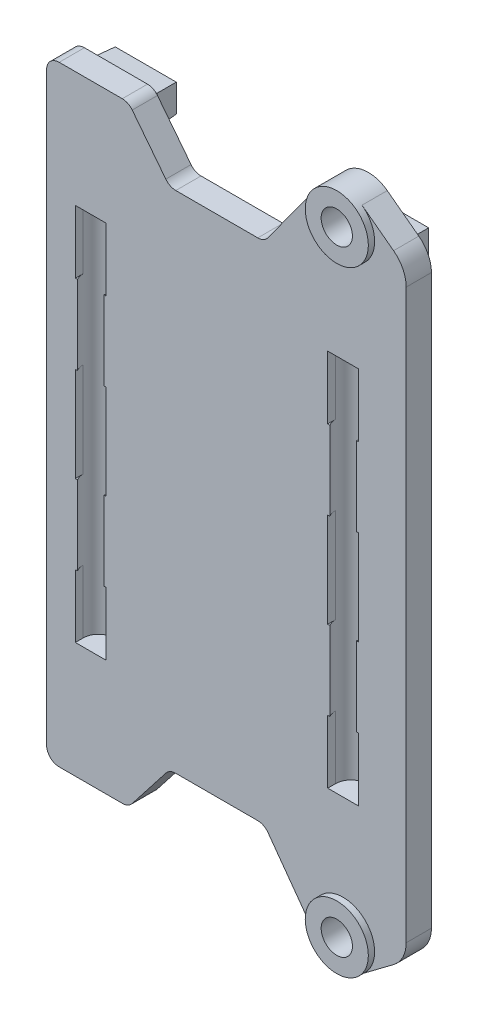
SolidWorks part; units mm, degrees
ref_plane "Front Plane" through (0, 0, 0) normal (0, 0, 1) x (1, 0, 0)
ref_plane "Top Plane" through (0, 0, 0) normal (0, 1, 0) x (1, 0, 0)
ref_plane "Right Plane" through (0, 0, 0) normal (1, 0, 0) x (0, 0, -1)
sketch "Sketch1" plane through (0, 0, 0) normal (0, 0, 1) x (1, 0, 0)
  line L0 (0, 0) -> (190.5, 0) construction
  line L1 (190.5, 28.575) -> (190.5, -28.575) construction
  line L2 (-190.5, -28.575) -> (-190.5, 28.575) construction
  line L3 (190.5, -25.4) -> (-190.5, -25.4) construction
  line L4 (190.5, -25.4) -> (190.5, 25.4) construction
  line L5 (190.5, 25.4) -> (-190.5, 25.4) construction
  line L6 (-190.5, -25.4) -> (-190.5, 25.4) construction
  line L7 (190.5, -25.4) -> (-190.5, 25.4) construction
  line L8 (190.5, 25.4) -> (-190.5, -25.4) construction
  dimension "D1" = 50.8
sketch "Sketch2" plane through (0, 0, 0) normal (0, 0, 1) x (1, 0, 0)
  line L0 (190.5, 25.4) -> (-190.5, 25.4) construction
  line L1 (190.5, 28.575) -> (190.5, -28.575) construction
  line L2 (186.055, 33.4962) -> (189.23, 31.115)
  line L3 (190.5, 28.575) -> (190.5, 0)
  line L4 (190.5, 0) -> (154.305, 0)
  line L5 (0, 0) -> (190.5, 0) construction
  line L6 (154.305, 0) -> (154.305, 29.44)
  line L7 (155.575, 30.71) -> (161.925, 30.71)
  line L8 (162.9263, 30.2212) -> (166.3062, 25.8888)
  line L9 (167.3075, 25.4) -> (175.5637, 25.4)
  line L10 (176.5927, 25.9257) -> (181.5774, 32.817)
  line L13 (161.925, 29.44) -> (155.575, 29.44) construction
  line L14 (161.925, 29.44) -> (161.925, 26.44) construction
  line L15 (161.925, 26.44) -> (155.575, 26.44) construction
  line L16 (155.575, 29.44) -> (155.575, 26.44) construction
  line L17 (161.925, 29.44) -> (155.575, 26.44) construction
  line L18 (161.925, 26.44) -> (155.575, 29.44) construction
  circle A0 centre (184.15, 30.9562) radius 5.5563 construction
  circle A1 centre (184.15, 30.9562) radius 1.575
  circle A2 centre (184.15, 30.9562) radius 4.5 construction
  arc A4 (186.055, 33.4962) -> (181.5774, 32.817) centre (184.15, 30.9562) ccw
  arc A5 (189.23, 31.115) -> (190.5, 28.575) centre (187.325, 28.575) cw
  arc A6 (190.5, 28.575) -> (187.325, 31.75) centre (187.325, 28.575) ccw construction
  arc A7 (190.5, 28.575) -> (187.325, 31.75) centre (187.325, 28.575) ccw construction
  arc A8 (176.5927, 25.9257) -> (175.5637, 25.4) centre (175.5637, 26.67) cw
  arc A9 (167.3075, 25.4) -> (166.3062, 25.8888) centre (167.3075, 26.67) cw
  arc A10 (162.9263, 30.2212) -> (161.925, 30.71) centre (161.925, 29.44) ccw
  arc A11 (155.575, 30.71) -> (154.305, 29.44) centre (155.575, 29.44) ccw
  point P27 (158.75, 27.94)
  point P32 (176.2125, 25.4)
  point P36 (166.6875, 25.4)
  dimension "D1" = 3.15
  dimension "D2" = 11.1125
  dimension "D3" = 9
  dimension "D5" = 6.35
  dimension "D8" = 1.27
  dimension "D4" = 6.35
  dimension "D6" = 14.2875
  dimension "D7" = 9.525
  dimension "D9" = 31.75
  dimension "D10" = 6.35
  dimension "D11" = 3
  dimension "D12" = 2.54
extrude "Boss-Extrude1" add sketch "Sketch2" along normal blind 2.54 contours L7 A11 L6 L4 L3 A5 L2 A4 L10 A8 L9 A9 L8 A10
sketch "Sketch3" plane through (0, 0, 2.54) normal (0, 0, 1) x (1, 0, 0)
  circle A0 centre (184.15, 30.9562) radius 1.575
  circle A1 centre (184.15, 30.9562) radius 3.175
  circle A2 centre (184.15, 30.9562) radius 1.575 construction
extrude "Boss-Extrude2" add sketch "Sketch3" along normal offset from surface (0.635 mm away) 3.175 up to face at (185.725, 30.9562, 0)
sketch "Sketch4" plane through (0, 0, 0) normal (0, 0, -1) x (-1, 0, 0)
  line L0 (0, 0) -> (-190.5, 0) construction
  line L1 (-187.325, 29.44) -> (-180.975, 29.44)
  line L2 (-187.325, 29.44) -> (-187.325, 26.44)
  line L3 (-187.325, 26.44) -> (-180.975, 26.44)
  line L4 (-180.975, 29.44) -> (-180.975, 26.44)
  line L5 (-187.325, 29.44) -> (-180.975, 26.44) construction
  line L6 (-187.325, 26.44) -> (-180.975, 29.44) construction
  line L7 (-161.925, 29.44) -> (-155.575, 29.44)
  line L8 (-161.925, 29.44) -> (-161.925, 26.44)
  line L9 (-161.925, 26.44) -> (-155.575, 26.44)
  line L10 (-155.575, 29.44) -> (-155.575, 26.44)
  line L11 (-161.925, 29.44) -> (-155.575, 26.44) construction
  line L12 (-161.925, 26.44) -> (-155.575, 29.44) construction
  line L13 (-190.5, -25.4) -> (-190.5, 25.4) construction
  point P0 (-184.15, 27.94)
  point P5 (-158.75, 27.94)
  dimension "D1" = 27.94
  dimension "D2" = 6.35
  dimension "D3" = 3
  dimension "D4" = 6.35
  dimension "D5" = 25.4
extrude "Boss-Extrude3" add sketch "Sketch4" along normal blind 1
sketch "Sketch5" plane through (0, 0, -1) normal (0, 0, -1) x (-1, 0, 0)
  line L0 (-155.575, 26.44) -> (-155.575, 29.44) construction
  line L1 (-155.575, 29.44) -> (-161.925, 29.44) construction
  line L2 (-161.925, 29.44) -> (-161.925, 26.44) construction
  line L3 (-161.925, 26.44) -> (-155.575, 26.44) construction
  line L4 (-180.975, 26.44) -> (-180.975, 29.44) construction
  line L5 (-180.975, 29.44) -> (-187.325, 29.44) construction
  line L6 (-187.325, 29.44) -> (-187.325, 26.44) construction
  line L7 (-187.325, 26.44) -> (-180.975, 26.44) construction
  line L8 (-155.575, 26.44) -> (-155.575, 29.44)
  line L9 (-155.575, 29.44) -> (-161.925, 29.44)
  line L10 (-161.925, 29.44) -> (-161.925, 26.44)
  line L11 (-161.925, 26.44) -> (-155.575, 26.44)
  line L12 (-180.975, 26.44) -> (-180.975, 29.44)
  line L13 (-180.975, 29.44) -> (-187.325, 29.44)
  line L14 (-187.325, 29.44) -> (-187.325, 26.44)
  line L15 (-187.325, 26.44) -> (-180.975, 26.44)
extrude "Boss-Extrude4" add sketch "Sketch5" along normal offset from surface 3 draft 3
sketch "Sketch6" plane through (0, 0, 0) normal (0, -1, 0) x (1, 0, 0)
  line L1 (190.5, 2.54) -> (190.5, 0) construction
  line L2 (190.5, 0) -> (154.305, 0) construction
  circle A0 centre (184.15, 1.752) radius 1.55
  point P5 (184.15, 3.302)
  dimension "D3" = 3.1
  dimension "D4" = 3.302
  dimension "D2" = 6.35
extrude "Cut-Extrude1" cut sketch "Sketch6" against normal blind 19.05
sketch "Sketch7" plane through (0, 0, 2.54) normal (0, 0, 1) x (1, 0, 0)
  line L0 (0, 0) -> (190.5, 0) construction
  line L1 (185.7, 12.7) -> (182.6, 12.7)
  line L2 (185.7, 12.7) -> (185.7, 19.05)
  line L3 (185.7, 19.05) -> (182.6, 19.05) construction
  line L4 (182.6, 12.7) -> (182.6, 19.05)
  line L5 (185.7, 12.7) -> (182.6, 19.05) construction
  line L6 (185.7, 19.05) -> (182.6, 12.7) construction
  line L7 (185.7, 4.7625) -> (182.6, 4.7625)
  line L8 (185.7, 4.7625) -> (185.7, 0)
  line L9 (185.7, 0) -> (182.6, 0)
  line L10 (182.6, 4.7625) -> (182.6, 0)
  line L11 (185.7, 4.7625) -> (182.6, 0) construction
  line L12 (185.7, 0) -> (182.6, 4.7625) construction
  line L13 (182.6, 19.05) -> (185.7, 19.05) construction
  line L14 (182.6, 19.05) -> (185.7, 19.05)
  point P0 (184.15, 15.875)
  point P5 (184.15, 2.3813)
  dimension "D1" = 6.35
  dimension "D2" = 4.7625
extrude "Cut-Extrude2" cut sketch "Sketch7" against normal up to next
sketch "Sketch8" plane through (0, 0, 2.54) normal (0, 0, 1) x (1, 0, 0)
  line L0 (0, 0) -> (190.5, 0) construction
  line L1 (183.515, 0) -> (184.785, 0)
  line L2 (183.515, 0) -> (183.515, 6.35)
  line L3 (183.515, 6.35) -> (184.785, 6.35)
  line L4 (184.785, 0) -> (184.785, 6.35)
  line L5 (183.515, 0) -> (184.785, 6.35) construction
  line L6 (183.515, 6.35) -> (184.785, 0) construction
  line L9 (184.15, 3.175) -> (184.15, 19.05) construction
  line L10 (182.6, 19.05) -> (185.7, 19.05) construction
  point P0 (184.15, 3.175)
  point P5 (184.15, 0)
  dimension "D1" = 6.35
  dimension "D2" = 1.27
extrude "Cut-Extrude3" cut sketch "Sketch8" against normal up to next
pattern_linear "LPattern1" count 2 spacing 25.4 along (-1, 0, 0) of "Cut-Extrude1", "Cut-Extrude2", "Cut-Extrude3"
mirror "Mirror1" about plane through (0, 0, 0) normal (0, 1, 0) of bodies 109 102
